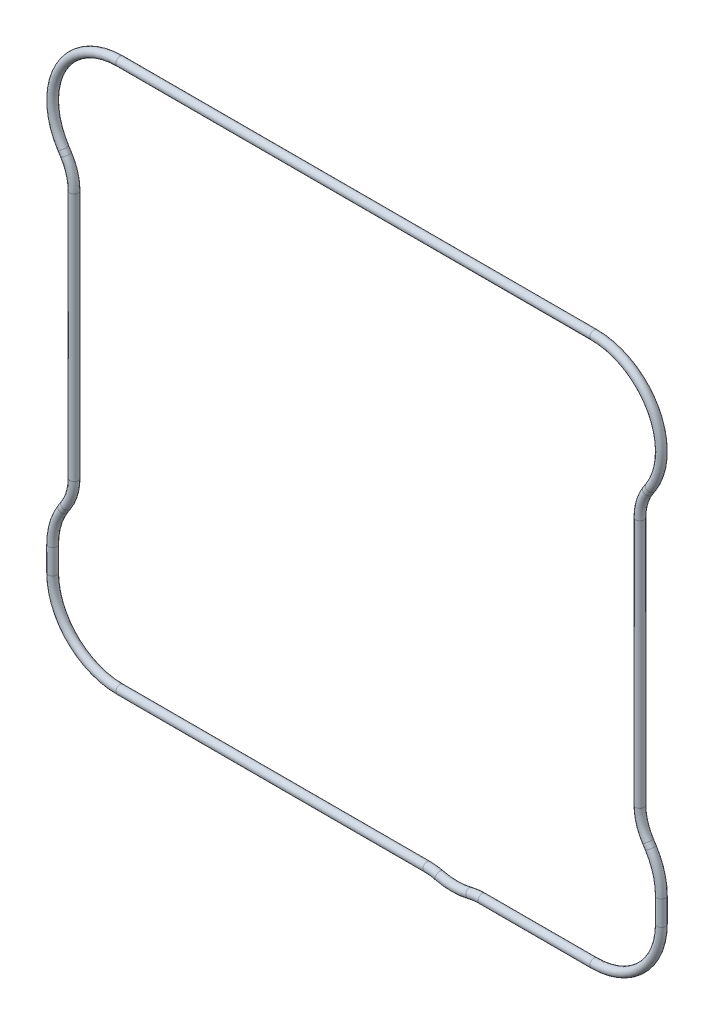
SolidWorks part; units mm, degrees
material "Rubber"
ref_plane "Front Plane" through (0, 0, 0) normal (0, 0, 1) x (1, 0, 0)
ref_plane "Top Plane" through (0, 0, 0) normal (0, 1, 0) x (1, 0, 0)
ref_plane "Right Plane" through (0, 0, 0) normal (1, 0, 0) x (0, 0, -1)
sketch "Sketch1" plane through (0, 0, 0) normal (0, 0, 1) x (1, 0, 0)
  line L10 (105.3385, -55.9782) -> (104.3317, -54.4056)
  line L30 (-105.3385, 55.9782) -> (-104.3317, 54.4056)
  line L31 (85, 93.15) -> (-85, 93.15)
  line L32 (104.3317, 54.4056) -> (105.3385, 55.9782)
  line L33 (101.475, -44.646) -> (101.475, 44.646)
  line L34 (109.15, -77.8) -> (109.15, -69)
  line L35 (44.8772, -101.95) -> (85, -101.95)
  line L36 (-85, -101.95) -> (25.1228, -101.95)
  line L37 (-109.15, -69) -> (-109.15, -77.8)
  line L38 (-104.3317, -54.4056) -> (-105.3385, -55.9782)
  line L39 (-101.475, 44.646) -> (-101.475, -44.646)
  arc A39 (-101.475, 44.646) -> (-104.3317, 54.4056) centre (-119.575, 44.646) ccw
  arc A40 (-85, 93.15) -> (-105.3385, 55.9782) centre (-85, 69) ccw
  arc A41 (105.3385, 55.9782) -> (85, 93.15) centre (85, 69) ccw
  arc A42 (104.3317, 54.4056) -> (101.475, 44.646) centre (119.575, 44.646) ccw
  arc A43 (101.475, -44.646) -> (104.3317, -54.4056) centre (119.575, -44.646) ccw
  arc A44 (109.15, -69) -> (105.3385, -55.9782) centre (85, -69) ccw
  arc A45 (85, -101.95) -> (109.15, -77.8) centre (85, -77.8) ccw
  arc A46 (44.8772, -101.95) -> (40.5432, -102.4765) centre (44.8772, -120.05) ccw
  arc A47 (29.4568, -102.4765) -> (25.1228, -101.95) centre (25.1228, -120.05) ccw
  arc A48 (29.4568, -102.4765) -> (40.5432, -102.4765) centre (35, -80) ccw
  arc A49 (-109.15, -77.8) -> (-85, -101.95) centre (-85, -77.8) ccw
  arc A50 (-105.3385, -55.9782) -> (-109.15, -69) centre (-85, -69) ccw
  arc A51 (-104.3317, -54.4056) -> (-101.475, -44.646) centre (-119.575, -44.646) ccw
sketch "Sketch2" plane through (0, 0, 0) normal (0, 1, 0) x (1, 0, 0)
  circle A0 centre (101.475, 0) radius 1.5
  dimension "D1" = 3
sweep "Sweep1" add profiles "Sketch2" path "Sketch1"
sketch "Sketch3" plane through (0, 0, 0) normal (0, 1, 0) x (1, 0, 0)
  line L0 (0, 0) -> (0, 48.4748) construction
  circle A0 centre (125, 0) radius 1.5
  dimension "D1" = 3
  dimension "D2" = 250
revolve "Revolve1" [suppressed] add sketch "Sketch3" angle 360 about L0
